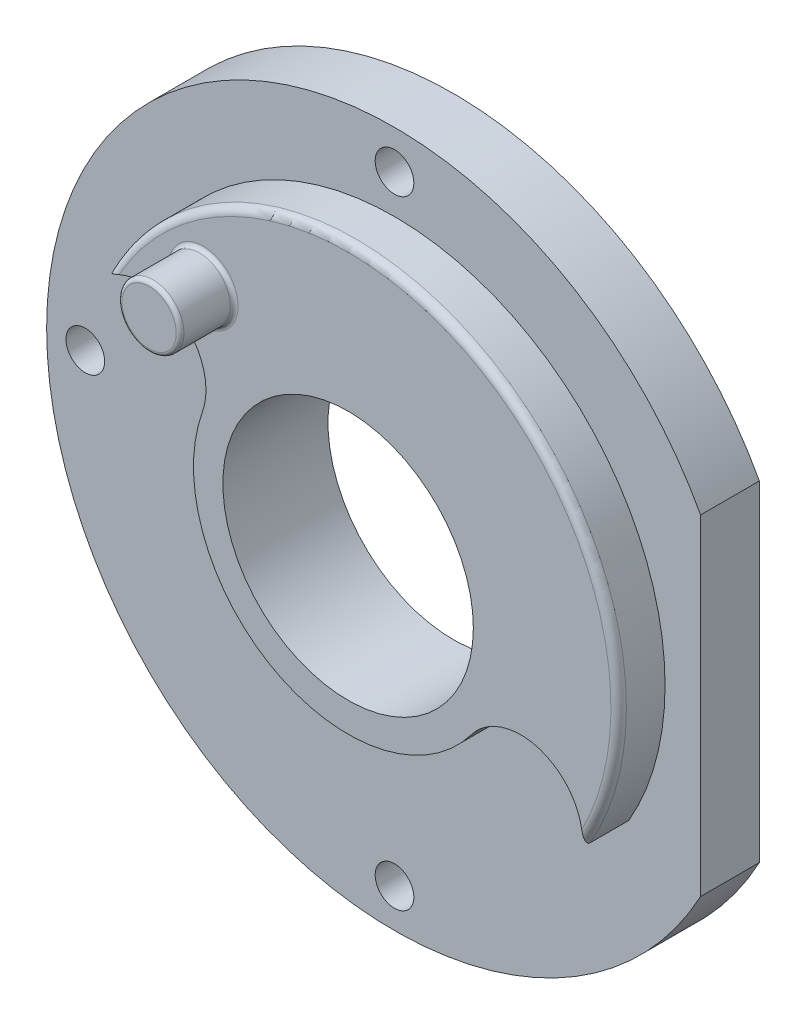
SolidWorks part; units mm, degrees
ref_plane "前视基准面" through (0, 0, 0) normal (0, 0, 1) x (1, 0, 0)
ref_plane "上视基准面" through (0, 0, 0) normal (0, 1, 0) x (1, 0, 0)
ref_plane "右视基准面" through (0, 0, 0) normal (1, 0, 0) x (0, 0, -1)
sketch "草图1" plane through (0, 0, 0) normal (0, 0, 1) x (1, 0, 0)
  circle A0 centre (0, 0) radius 20 construction
  circle A1 centre (0, 0) radius 22.5
  circle A2 centre (0, 20) radius 1.25
  circle A3 centre (0, -20) radius 1.25
  circle A5 centre (-20, 0) radius 1.25
  dimension "D1" = 40
  dimension "D2" = 45
  dimension "D3" = 2.5
  dimension "D4" = 2.5
extrude "凸台-拉伸1" add sketch "草图1" along normal blind 3.8
sketch "草图2" plane through (0, 0, 3.8) normal (0, 0, 1) x (1, 0, 0)
  circle A0 centre (0, 0) radius 17.5
  dimension "D1" = 35
extrude "凸台-拉伸2" add sketch "草图2" along normal blind 3
sketch "草图3" plane through (0, 0, 6.8) normal (0, 0, 1) x (1, 0, 0)
  line L0 (0, 0) -> (-4.6023, 0) construction
  line L1 (0, 0) -> (-9.3678, 10.404) construction
  circle A0 centre (0, 0) radius 14 construction
  circle A1 centre (-9.3678, 10.404) radius 2
  dimension "D1" = 28
  dimension "D2" = 4
  dimension "D3" = 48
extrude "凸台-拉伸3" add sketch "草图3" along normal blind 3.5
fillet "圆角1" radius 0.5 1 edges at (17.5, 0, 6.8)
fillet "圆角2" radius 0.25 2 edges at (-7.3678, 10.404, 6.8) (-7.3678, 10.404, 10.3)
sketch "草图4" plane through (0, 0, 6.8) normal (0, 0, 1) x (1, 0, 0)
  line L0 (-11.3299, 8.224) -> (0, 0) construction
  line L1 (0, 0) -> (13.0988, -4.9417) construction
  circle A0 centre (0, 0) radius 14 construction
  arc A1 (11.1668, -8.4441) -> (-13.193, 4.6844) centre (0, 0) cw construction
  arc A2 (-16.9625, 6.0228) -> (14.3573, -10.8567) centre (0, 0) ccw
  arc A3 (-9.4236, 3.346) -> (7.9763, -6.0315) centre (0, 0) ccw
  arc A4 (-9.4236, 3.346) -> (-16.9625, 6.0228) centre (-13.193, 4.6844) ccw
  arc A5 (14.3573, -10.8567) -> (7.9763, -6.0315) centre (11.1668, -8.4441) ccw
  point P5 (-6.642, -12.3241)
  point P10 (-11.3299, 8.224)
  point P12 (13.0988, -4.9417)
  dimension "D1" = 28
  dimension "D2" = 4
extrude "切除-拉伸1" cut sketch "草图4" against normal blind 3
sketch "草图5" plane through (0, 0, 6.8) normal (0, 0, 1) x (1, 0, 0)
  circle A0 centre (0, 0) radius 8.1
  dimension "D1" = 16.2
extrude "切除-拉伸2" cut sketch "草图5" against normal blind 11
sketch "草图6" plane through (0, 0, 3.8) normal (0, 0, 1) x (1, 0, 0)
  line L1 (19.8, -17.9414) -> (30.0832, -17.9414)
  line L2 (19.8, -17.9414) -> (19.8, 16.0471)
  line L3 (19.8, 16.0471) -> (30.0832, 16.0471)
  line L4 (30.0832, -17.9414) -> (30.0832, 16.0471)
  circle A0 centre (0, 0) radius 8.1 construction
  dimension "D1" = 19.8
extrude "切除-拉伸3" cut sketch "草图6" against normal blind 17
